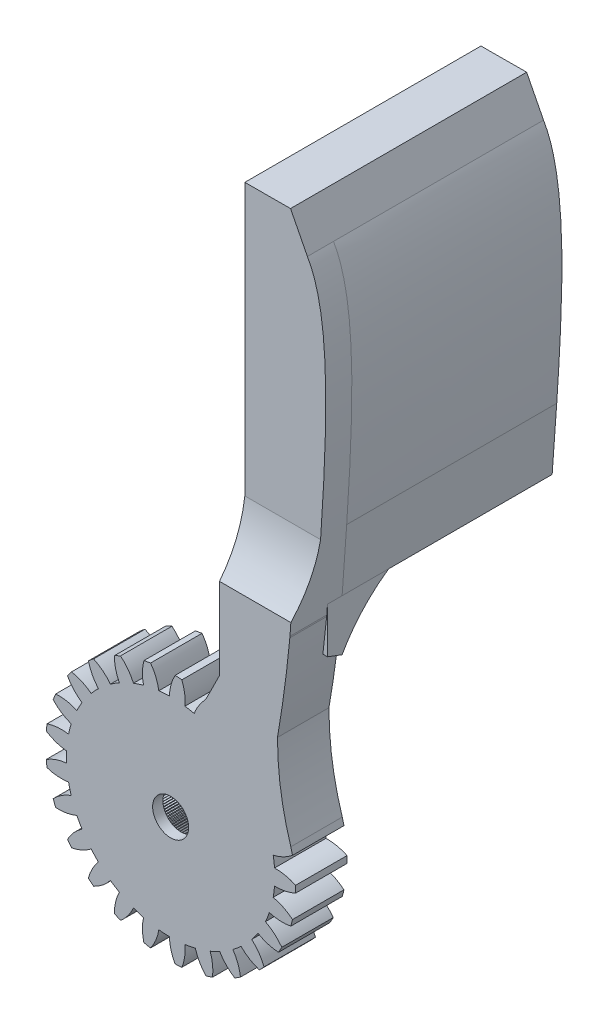
SolidWorks part; units mm, degrees
ref_plane "Front Plane" through (0, 0, 0) normal (0, 0, 1) x (1, 0, 0)
ref_plane "Top Plane" through (0, 0, 0) normal (0, 1, 0) x (1, 0, 0)
ref_plane "Right Plane" through (0, 0, 0) normal (1, 0, 0) x (0, 0, -1)
sketch "Sketch1" plane through (0, 0, 0) normal (0, 0, 1) x (1, 0, 0)
  line L400 (11.1072, 2.7986) -> (11.0109, 2.9361)
  line L401 (11.0109, 2.9361) -> (10.9327, 2.7877)
  line L402 (10.9327, 2.7877) -> (10.828, 2.9188)
  line L403 (10.828, 2.9188) -> (10.7592, 2.7657)
  line L404 (10.7592, 2.7657) -> (10.6465, 2.89)
  line L405 (10.6465, 2.89) -> (10.5874, 2.733)
  line L406 (10.5874, 2.733) -> (10.4672, 2.8499)
  line L407 (10.4672, 2.8499) -> (10.4181, 2.6895)
  line L408 (10.4181, 2.6895) -> (10.2907, 2.7987)
  line L409 (10.2907, 2.7987) -> (10.2518, 2.6355)
  line L410 (10.2518, 2.6355) -> (10.1178, 2.7364)
  line L411 (10.1178, 2.7364) -> (10.0893, 2.5711)
  line L412 (10.0893, 2.5711) -> (9.9492, 2.6635)
  line L413 (9.9492, 2.6635) -> (9.9311, 2.4967)
  line L414 (9.9311, 2.4967) -> (9.7855, 2.58)
  line L415 (9.7855, 2.58) -> (9.7778, 2.4124)
  line L416 (9.7778, 2.4124) -> (9.6273, 2.4865)
  line L417 (9.6273, 2.4865) -> (9.6302, 2.3187)
  line L418 (9.6302, 2.3187) -> (9.4753, 2.3832)
  line L419 (9.4753, 2.3832) -> (9.4888, 2.216)
  line L420 (9.4888, 2.216) -> (9.3301, 2.2706)
  line L421 (9.3301, 2.2706) -> (9.354, 2.1045)
  line L422 (9.354, 2.1045) -> (9.1923, 2.1491)
  line L423 (9.1923, 2.1491) -> (9.2266, 1.9848)
  line L424 (9.2266, 1.9848) -> (9.0624, 2.0191)
  line L425 (9.0624, 2.0191) -> (9.1069, 1.8574)
  line L426 (9.1069, 1.8574) -> (8.9408, 1.8813)
  line L427 (8.9408, 1.8813) -> (8.9955, 1.7227)
  line L428 (8.9955, 1.7227) -> (8.8282, 1.7361)
  line L429 (8.8282, 1.7361) -> (8.8927, 1.5812)
  line L430 (8.8927, 1.5812) -> (8.7249, 1.5841)
  line L431 (8.7249, 1.5841) -> (8.799, 1.4336)
  line L432 (8.799, 1.4336) -> (8.6314, 1.426)
  line L433 (8.6314, 1.426) -> (8.7148, 1.2804)
  line L434 (8.7148, 1.2804) -> (8.548, 1.2623)
  line L435 (8.548, 1.2623) -> (8.6403, 1.1222)
  line L436 (8.6403, 1.1222) -> (8.475, 1.0936)
  line L437 (8.475, 1.0936) -> (8.576, 0.9596)
  line L438 (8.576, 0.9596) -> (8.4128, 0.9207)
  line L439 (8.4128, 0.9207) -> (8.5219, 0.7933)
  line L440 (8.5219, 0.7933) -> (8.3615, 0.7443)
  line L441 (8.3615, 0.7443) -> (8.4785, 0.624)
  line L442 (8.4785, 0.624) -> (8.3214, 0.565)
  line L443 (8.3214, 0.565) -> (8.4457, 0.4522)
  line L444 (8.4457, 0.4522) -> (8.2927, 0.3835)
  line L445 (8.2927, 0.3835) -> (8.4238, 0.2788)
  line L446 (8.4238, 0.2788) -> (8.2754, 0.2005)
  line L447 (8.2754, 0.2005) -> (8.4128, 0.1043)
  line L448 (8.4128, 0.1043) -> (8.2696, 0.0169)
  line L449 (8.2696, 0.0169) -> (8.4128, -0.0706)
  line L450 (8.4128, -0.0706) -> (8.2754, -0.1668)
  line L451 (8.2754, -0.1668) -> (8.4238, -0.245)
  line L452 (8.4238, -0.245) -> (8.2927, -0.3497)
  line L453 (8.2927, -0.3497) -> (8.4457, -0.4185)
  line L454 (8.4457, -0.4185) -> (8.3214, -0.5312)
  line L455 (8.3214, -0.5312) -> (8.4785, -0.5903)
  line L456 (8.4785, -0.5903) -> (8.3615, -0.7105)
  line L457 (8.3615, -0.7105) -> (8.5219, -0.7596)
  line L458 (8.5219, -0.7596) -> (8.4128, -0.887)
  line L459 (8.4128, -0.887) -> (8.576, -0.9259)
  line L460 (8.576, -0.9259) -> (8.475, -1.0599)
  line L461 (8.475, -1.0599) -> (8.6403, -1.0884)
  line L462 (8.6403, -1.0884) -> (8.548, -1.2285)
  line L463 (8.548, -1.2285) -> (8.7148, -1.2466)
  line L464 (8.7148, -1.2466) -> (8.6314, -1.3922)
  line L465 (8.6314, -1.3922) -> (8.799, -1.3999)
  line L466 (8.799, -1.3999) -> (8.7249, -1.5504)
  line L467 (8.7249, -1.5504) -> (8.8927, -1.5475)
  line L468 (8.8927, -1.5475) -> (8.8282, -1.7024)
  line L469 (8.8282, -1.7024) -> (8.9955, -1.6889)
  line L470 (8.9955, -1.6889) -> (8.9408, -1.8476)
  line L471 (8.9408, -1.8476) -> (9.1069, -1.8237)
  line L472 (9.1069, -1.8237) -> (9.0624, -1.9854)
  line L473 (9.0624, -1.9854) -> (9.2266, -1.9511)
  line L474 (9.2266, -1.9511) -> (9.1923, -2.1153)
  line L475 (9.1923, -2.1153) -> (9.354, -2.0708)
  line L476 (9.354, -2.0708) -> (9.3301, -2.2369)
  line L477 (9.3301, -2.2369) -> (9.4888, -2.1822)
  line L478 (9.4888, -2.1822) -> (9.4753, -2.3495)
  line L479 (9.4753, -2.3495) -> (9.6302, -2.285)
  line L480 (9.6302, -2.285) -> (9.6273, -2.4528)
  line L481 (9.6273, -2.4528) -> (9.7778, -2.3787)
  line L482 (9.7778, -2.3787) -> (9.7855, -2.5463)
  line L483 (9.7855, -2.5463) -> (9.9311, -2.4629)
  line L484 (9.9311, -2.4629) -> (9.9492, -2.6297)
  line L485 (9.9492, -2.6297) -> (10.0893, -2.5374)
  line L486 (10.0893, -2.5374) -> (10.1178, -2.7027)
  line L487 (10.1178, -2.7027) -> (10.2518, -2.6017)
  line L488 (10.2518, -2.6017) -> (10.2907, -2.7649)
  line L489 (10.2907, -2.7649) -> (10.4181, -2.6558)
  line L490 (10.4181, -2.6558) -> (10.4672, -2.8162)
  line L491 (10.4672, -2.8162) -> (10.5874, -2.6992)
  line L492 (10.5874, -2.6992) -> (10.6465, -2.8563)
  line L493 (10.6465, -2.8563) -> (10.7592, -2.732)
  line L494 (10.7592, -2.732) -> (10.828, -2.885)
  line L495 (10.828, -2.885) -> (10.9327, -2.7539)
  line L496 (10.9327, -2.7539) -> (11.0109, -2.9023)
  line L497 (11.0109, -2.9023) -> (11.1072, -2.7649)
  line L498 (11.1072, -2.7649) -> (11.1946, -2.9081)
  line L499 (11.1946, -2.9081) -> (11.282, -2.7649)
  line L500 (11.282, -2.7649) -> (11.3782, -2.9023)
  line L501 (11.3782, -2.9023) -> (11.4565, -2.7539)
  line L502 (11.4565, -2.7539) -> (11.5612, -2.885)
  line L503 (11.5612, -2.885) -> (11.6299, -2.732)
  line L504 (11.6299, -2.732) -> (11.7427, -2.8563)
  line L505 (11.7427, -2.8563) -> (11.8017, -2.6992)
  line L506 (11.8017, -2.6992) -> (11.922, -2.8162)
  line L507 (11.922, -2.8162) -> (11.971, -2.6558)
  line L508 (11.971, -2.6558) -> (12.0984, -2.7649)
  line L509 (12.0984, -2.7649) -> (12.1373, -2.6017)
  line L510 (12.1373, -2.6017) -> (12.2713, -2.7027)
  line L511 (12.2713, -2.7027) -> (12.2999, -2.5374)
  line L512 (12.2999, -2.5374) -> (12.44, -2.6297)
  line L513 (12.44, -2.6297) -> (12.4581, -2.4629)
  line L514 (12.4581, -2.4629) -> (12.6037, -2.5463)
  line L515 (12.6037, -2.5463) -> (12.6113, -2.3787)
  line L516 (12.6113, -2.3787) -> (12.7618, -2.4528)
  line L517 (12.7618, -2.4528) -> (12.7589, -2.285)
  line L518 (12.7589, -2.285) -> (12.9138, -2.3495)
  line L519 (12.9138, -2.3495) -> (12.9004, -2.1822)
  line L520 (12.9004, -2.1822) -> (13.059, -2.2369)
  line L521 (13.059, -2.2369) -> (13.0351, -2.0708)
  line L522 (13.0351, -2.0708) -> (13.1968, -2.1153)
  line L523 (13.1968, -2.1153) -> (13.1625, -1.9511)
  line L524 (13.1625, -1.9511) -> (13.3268, -1.9854)
  line L525 (13.3268, -1.9854) -> (13.2822, -1.8237)
  line L526 (13.2822, -1.8237) -> (13.4483, -1.8476)
  line L527 (13.4483, -1.8476) -> (13.3937, -1.6889)
  line L528 (13.3937, -1.6889) -> (13.5609, -1.7024)
  line L529 (13.5609, -1.7024) -> (13.4965, -1.5475)
  line L530 (13.4965, -1.5475) -> (13.6642, -1.5504)
  line L531 (13.6642, -1.5504) -> (13.5901, -1.3999)
  line L532 (13.5901, -1.3999) -> (13.7577, -1.3922)
  line L533 (13.7577, -1.3922) -> (13.6744, -1.2466)
  line L534 (13.6744, -1.2466) -> (13.8412, -1.2285)
  line L535 (13.8412, -1.2285) -> (13.7488, -1.0884)
  line L536 (13.7488, -1.0884) -> (13.9141, -1.0599)
  line L537 (13.9141, -1.0599) -> (13.8132, -0.9259)
  line L538 (13.8132, -0.9259) -> (13.9764, -0.887)
  line L539 (13.9764, -0.887) -> (13.8672, -0.7596)
  line L540 (13.8672, -0.7596) -> (14.0276, -0.7105)
  line L541 (14.0276, -0.7105) -> (13.9107, -0.5903)
  line L542 (13.9107, -0.5903) -> (14.0677, -0.5312)
  line L543 (14.0677, -0.5312) -> (13.9434, -0.4185)
  line L544 (13.9434, -0.4185) -> (14.0965, -0.3497)
  line L545 (14.0965, -0.3497) -> (13.9654, -0.245)
  line L546 (13.9654, -0.245) -> (14.1138, -0.1668)
  line L547 (14.1138, -0.1668) -> (13.9763, -0.0706)
  line L548 (13.9763, -0.0706) -> (14.1195, 0.0169)
  line L549 (14.1195, 0.0169) -> (13.9763, 0.1043)
  line L550 (13.9763, 0.1043) -> (14.1138, 0.2005)
  line L551 (14.1138, 0.2005) -> (13.9654, 0.2788)
  line L552 (13.9654, 0.2788) -> (14.0965, 0.3835)
  line L553 (14.0965, 0.3835) -> (13.9434, 0.4522)
  line L554 (13.9434, 0.4522) -> (14.0677, 0.565)
  line L555 (14.0677, 0.565) -> (13.9107, 0.624)
  line L556 (13.9107, 0.624) -> (14.0276, 0.7443)
  line L557 (14.0276, 0.7443) -> (13.8672, 0.7933)
  line L558 (13.8672, 0.7933) -> (13.9764, 0.9207)
  line L559 (13.9764, 0.9207) -> (13.8132, 0.9596)
  line L560 (13.8132, 0.9596) -> (13.9141, 1.0936)
  line L561 (13.9141, 1.0936) -> (13.7488, 1.1222)
  line L562 (13.7488, 1.1222) -> (13.8412, 1.2623)
  line L563 (13.8412, 1.2623) -> (13.6744, 1.2804)
  line L564 (13.6744, 1.2804) -> (13.7577, 1.426)
  line L565 (13.7577, 1.426) -> (13.5901, 1.4336)
  line L566 (13.5901, 1.4336) -> (13.6642, 1.5841)
  line L567 (13.6642, 1.5841) -> (13.4965, 1.5812)
  line L568 (13.4965, 1.5812) -> (13.5609, 1.7361)
  line L569 (13.5609, 1.7361) -> (13.3937, 1.7227)
  line L570 (13.3937, 1.7227) -> (13.4483, 1.8813)
  line L571 (13.4483, 1.8813) -> (13.2822, 1.8574)
  line L572 (13.2822, 1.8574) -> (13.3268, 2.0191)
  line L573 (13.3268, 2.0191) -> (13.1625, 1.9848)
  line L574 (13.1625, 1.9848) -> (13.1968, 2.1491)
  line L575 (13.1968, 2.1491) -> (13.0351, 2.1045)
  line L576 (13.0351, 2.1045) -> (13.059, 2.2706)
  line L577 (13.059, 2.2706) -> (12.9004, 2.216)
  line L578 (12.9004, 2.216) -> (12.9138, 2.3832)
  line L579 (12.9138, 2.3832) -> (12.7589, 2.3187)
  line L580 (12.7589, 2.3187) -> (12.7618, 2.4865)
  line L581 (12.7618, 2.4865) -> (12.6113, 2.4124)
  line L582 (12.6113, 2.4124) -> (12.6037, 2.58)
  line L583 (12.6037, 2.58) -> (12.4581, 2.4967)
  line L584 (12.4581, 2.4967) -> (12.44, 2.6635)
  line L585 (12.44, 2.6635) -> (12.2999, 2.5711)
  line L586 (12.2999, 2.5711) -> (12.2713, 2.7364)
  line L587 (12.2713, 2.7364) -> (12.1373, 2.6355)
  line L588 (12.1373, 2.6355) -> (12.0984, 2.7987)
  line L589 (12.0984, 2.7987) -> (11.971, 2.6895)
  line L590 (11.971, 2.6895) -> (11.922, 2.8499)
  line L591 (11.922, 2.8499) -> (11.8017, 2.733)
  line L592 (11.8017, 2.733) -> (11.7427, 2.89)
  line L593 (11.7427, 2.89) -> (11.6299, 2.7657)
  line L594 (11.6299, 2.7657) -> (11.5612, 2.9188)
  line L595 (11.5612, 2.9188) -> (11.4565, 2.7877)
  line L596 (11.4565, 2.7877) -> (11.3782, 2.9361)
  line L597 (11.3782, 2.9361) -> (11.282, 2.7986)
  line L598 (11.282, 2.7986) -> (11.1946, 2.9418)
  line L599 (11.1946, 2.9418) -> (11.1072, 2.7986)
  circle A1 centre (11.1946, 0) radius 1.8
  arc A202 (10.0473, 10.0588) -> (9.2444, 11.9925) centre (5.6039, 9.3473) ccw
  arc A203 (9.2444, 11.9925) -> (8.5931, 11.8682) centre (11.1946, 0) ccw
  arc A204 (8.5931, 11.8682) -> (8.5584, 9.7748) centre (12.9517, 10.749) ccw
  arc A205 (8.5584, 9.7748) -> (7.5818, 9.4575) centre (11.1946, 0) ccw
  arc A206 (7.5818, 9.4575) -> (6.3233, 11.1307) centre (3.455, 7.6633) ccw
  arc A207 (6.3233, 11.1307) -> (5.7233, 10.8484) centre (11.1946, 0) ccw
  arc A208 (5.7233, 10.8484) -> (6.2103, 8.8121) centre (10.2233, 10.8483) ccw
  arc A209 (6.2103, 8.8121) -> (5.3434, 8.2619) centre (11.1946, 0) ccw
  arc A210 (5.3434, 8.2619) -> (3.7082, 9.5696) centre (1.7923, 5.4978) ccw
  arc A211 (3.7082, 9.5696) -> (3.1973, 9.1469) centre (11.1946, 0) ccw
  arc A212 (3.1973, 9.1469) -> (4.1754, 7.2957) centre (7.556, 10.2659) ccw
  arc A213 (4.1754, 7.2957) -> (3.4725, 6.5472) centre (11.1946, 0) ccw
  arc A214 (3.4725, 6.5472) -> (1.5636, 7.4072) centre (0.7205, 2.9868) ccw
  arc A215 (1.5636, 7.4072) -> (1.1738, 6.8707) centre (11.1946, 0) ccw
  arc A216 (1.1738, 6.8707) -> (2.5816, 5.3209) centre (5.1172, 9.0385) ccw
  arc A217 (2.5816, 5.3209) -> (2.0869, 4.4211) centre (11.1946, 0) ccw
  arc A218 (2.0869, 4.4211) -> (0.024, 4.7793) centre (0.3067, 0.2882) ccw
  arc A219 (0.024, 4.7793) -> (-0.2201, 4.1628) centre (11.1946, 0) ccw
  arc A220 (-0.2201, 4.1628) -> (1.5289, 3.0118) centre (3.0604, 7.2432) ccw
  arc A221 (1.5289, 3.0118) -> (1.2736, 2.0172) centre (11.1946, 0) ccw
  arc A222 (1.2736, 2.0172) -> (-0.8136, 1.8512) centre (0.5771, -2.4286) ccw
  arc A223 (-0.8136, 1.8512) -> (-0.8967, 1.1933) centre (11.1946, 0) ccw
  arc A224 (-0.8967, 1.1933) -> (1.0836, 0.5134) centre (1.5146, 4.9927) ccw
  arc A225 (1.0836, 0.5134) -> (1.0836, -0.5134) centre (11.1946, 0) ccw
  arc A226 (1.0836, -0.5134) -> (-0.8967, -1.1933) centre (1.5146, -4.9927) ccw
  arc A227 (-0.8967, -1.1933) -> (-0.8136, -1.8512) centre (11.1946, 0) ccw
  arc A228 (-0.8136, -1.8512) -> (1.2736, -2.0172) centre (0.5771, 2.4286) ccw
  arc A229 (1.2736, -2.0172) -> (1.5289, -3.0118) centre (11.1946, 0) ccw
  arc A230 (1.5289, -3.0118) -> (-0.2201, -4.1628) centre (3.0604, -7.2432) ccw
  arc A231 (-0.2201, -4.1628) -> (0.024, -4.7793) centre (11.1946, 0) ccw
  arc A232 (0.024, -4.7793) -> (2.0869, -4.4211) centre (0.3067, -0.2882) ccw
  arc A233 (2.0869, -4.4211) -> (2.5816, -5.3209) centre (11.1946, 0) ccw
  arc A234 (2.5816, -5.3209) -> (1.1738, -6.8707) centre (5.1172, -9.0385) ccw
  arc A235 (1.1738, -6.8707) -> (1.5636, -7.4072) centre (11.1946, 0) ccw
  arc A236 (1.5636, -7.4072) -> (3.4725, -6.5472) centre (0.7205, -2.9868) ccw
  arc A237 (3.4725, -6.5472) -> (4.1754, -7.2957) centre (11.1946, 0) ccw
  arc A238 (4.1754, -7.2957) -> (3.1973, -9.1469) centre (7.556, -10.2659) ccw
  arc A239 (3.1973, -9.1469) -> (3.7082, -9.5696) centre (11.1946, 0) ccw
  arc A240 (3.7082, -9.5696) -> (5.3434, -8.2619) centre (1.7923, -5.4978) ccw
  arc A241 (5.3434, -8.2619) -> (6.2103, -8.8121) centre (11.1946, 0) ccw
  arc A242 (6.2103, -8.8121) -> (5.7233, -10.8484) centre (10.2233, -10.8483) ccw
  arc A243 (5.7233, -10.8484) -> (6.3233, -11.1307) centre (11.1946, 0) ccw
  arc A244 (6.3233, -11.1307) -> (7.5818, -9.4575) centre (3.455, -7.6633) ccw
  arc A245 (7.5818, -9.4575) -> (8.5584, -9.7748) centre (11.1946, 0) ccw
  arc A246 (8.5584, -9.7748) -> (8.5931, -11.8682) centre (12.9517, -10.749) ccw
  arc A247 (8.5931, -11.8682) -> (9.2444, -11.9925) centre (11.1946, 0) ccw
  arc A248 (9.2444, -11.9925) -> (10.0473, -10.0588) centre (5.6039, -9.3473) ccw
  arc A249 (10.0473, -10.0588) -> (11.0721, -10.1233) centre (11.1946, 0) ccw
  arc A250 (11.0721, -10.1233) -> (11.6263, -12.1423) centre (15.5696, -9.9743) ccw
  arc A251 (11.6263, -12.1423) -> (12.2881, -12.1007) centre (11.1946, 0) ccw
  arc A252 (12.2881, -12.1007) -> (12.5849, -10.0281) centre (8.1041, -10.444) ccw
  arc A253 (12.5849, -10.0281) -> (13.5935, -9.8357) centre (11.1946, 0) ccw
  arc A254 (13.5935, -9.8357) -> (14.6324, -11.6535) centre (17.9127, -8.5729) ccw
  arc A255 (14.6324, -11.6535) -> (15.263, -11.4486) centre (11.1946, 0) ccw
  arc A256 (15.263, -11.4486) -> (15.0351, -9.3673) centre (10.7985, -10.8845) ccw
  arc A257 (15.0351, -9.3673) -> (15.9642, -8.9301) centre (11.1946, 0) ccw
  arc A258 (15.9642, -8.9301) -> (17.4225, -10.4324) centre (19.8336, -6.6329) ccw
  arc A259 (17.4225, -10.4324) -> (17.9824, -10.0771) centre (11.1946, 0) ccw
  arc A260 (17.9824, -10.0771) -> (17.244, -8.1179) centre (13.5178, -10.641) ccw
  arc A261 (17.244, -8.1179) -> (18.0351, -7.4634) centre (11.1946, 0) ccw
  arc A262 (18.0351, -7.4634) -> (19.8213, -8.5558) centre (21.2117, -4.276) ccw
  arc A263 (19.8213, -8.5558) -> (20.2752, -8.0725) centre (11.1946, 0) ccw
  arc A264 (20.2752, -8.0725) -> (19.0727, -6.3584) centre (16.0912, -9.7289) ccw
  arc A265 (19.0727, -6.3584) -> (19.6763, -5.5277) centre (11.1946, 0) ccw
  arc A266 (19.6763, -5.5277) -> (21.678, -6.1417) centre (21.9604, -1.6505) ccw
  arc A267 (21.678, -6.1417) -> (21.9975, -5.5606) centre (11.1946, 0) ccw
  arc A268 (21.9975, -5.5606) -> (20.4065, -4.1994) centre (18.3568, -8.2055) ccw
  arc A269 (20.4065, -4.1994) -> (20.7845, -3.2447) centre (11.1946, 0) ccw
  arc A270 (20.7845, -3.2447) -> (22.876, -3.3416) centre (22.0327, 1.0787) ccw
  arc A271 (22.876, -3.3416) -> (23.0409, -2.6993) centre (11.1946, 0) ccw
  arc A272 (23.0409, -2.6993) -> (21.1615, -1.7766) centre (20.1724, -6.1666) ccw
  arc A273 (21.1615, -1.7766) -> (21.2902, -0.7579) centre (11.1946, 0) ccw
  arc A274 (21.2902, -0.7579) -> (23.34, -0.3315) centre (21.4239, 3.7401) ccw
  arc A275 (23.34, -0.3315) -> (23.34, 0.3315) centre (11.1946, 0) ccw
  arc A276 (23.34, 0.3315) -> (21.2902, 0.7579) centre (21.4239, -3.7401) ccw
  arc A277 (21.2902, 0.7579) -> (21.1615, 1.7766) centre (11.1946, 0) ccw
  arc A278 (21.1615, 1.7766) -> (23.0409, 2.6993) centre (20.1724, 6.1666) ccw
  arc A279 (23.0409, 2.6993) -> (22.876, 3.3416) centre (11.1946, 0) ccw
  arc A280 (22.876, 3.3416) -> (20.7845, 3.2447) centre (22.0327, -1.0787) ccw
  arc A281 (20.7845, 3.2447) -> (20.4065, 4.1994) centre (11.1946, 0) ccw
  arc A282 (20.4065, 4.1994) -> (21.9975, 5.5606) centre (18.3568, 8.2055) ccw
  arc A283 (21.9975, 5.5606) -> (21.678, 6.1417) centre (11.1946, 0) ccw
  arc A284 (21.678, 6.1417) -> (19.6763, 5.5277) centre (21.9604, 1.6505) ccw
  arc A285 (19.6763, 5.5277) -> (19.0727, 6.3584) centre (11.1946, 0) ccw
  arc A286 (19.0727, 6.3584) -> (20.2752, 8.0725) centre (16.0912, 9.7289) ccw
  arc A287 (20.2752, 8.0725) -> (19.8213, 8.5558) centre (11.1946, 0) ccw
  arc A288 (19.8213, 8.5558) -> (18.0351, 7.4634) centre (21.2117, 4.276) ccw
  arc A289 (18.0351, 7.4634) -> (17.244, 8.1179) centre (11.1946, 0) ccw
  arc A290 (17.244, 8.1179) -> (17.9824, 10.0771) centre (13.5178, 10.641) ccw
  arc A291 (17.9824, 10.0771) -> (17.4225, 10.4324) centre (11.1946, 0) ccw
  arc A292 (17.4225, 10.4324) -> (15.9642, 8.9301) centre (19.8336, 6.6329) ccw
  arc A293 (15.9642, 8.9301) -> (15.0351, 9.3673) centre (11.1946, 0) ccw
  arc A294 (15.0351, 9.3673) -> (15.263, 11.4486) centre (10.7985, 10.8845) ccw
  arc A295 (15.263, 11.4486) -> (14.6324, 11.6535) centre (11.1946, 0) ccw
  arc A296 (14.6324, 11.6535) -> (13.5935, 9.8357) centre (17.9127, 8.5729) ccw
  arc A297 (13.5935, 9.8357) -> (12.5849, 10.0281) centre (11.1946, 0) ccw
  arc A298 (12.5849, 10.0281) -> (12.2881, 12.1007) centre (8.1041, 10.444) ccw
  arc A299 (12.2881, 12.1007) -> (11.6263, 12.1423) centre (11.1946, 0) ccw
  arc A300 (11.6263, 12.1423) -> (11.0721, 10.1233) centre (15.5696, 9.9743) ccw
  arc A301 (11.0721, 10.1233) -> (10.0473, 10.0588) centre (11.1946, 0) ccw
extrude "Boss-Extrude1" add sketch "Sketch1" against normal blind 3.5 and the other way blind 1.5 contours A300 A301 A202 A203 A204 A205 A206 A207 A208 A209 A210 A211 A212 A213 A214 A215 A216 A217 A218 A219 A220 A221 A222 A223 A224 A225 A226 A227 A228 A229 A230 A231 A232 A233 A234 A235 A236 A237 A238 A239 A240 A241 A242 A243 A244 A245 A246 A247 A248 A249 A250
sketch "Sketch2" plane through (0, 0, 1.5) normal (0, 0, 1) x (1, 0, 0)
  circle A0 centre (11.1946, 0) radius 4.0084
  circle A1 centre (11.1946, 0) radius 1.75
  point P4 (0, 0)
  point P5 (11.1946, 0)
  dimension "D1" = 3.5
extrude "Boss-Extrude2" add sketch "Sketch2" against normal blind 1
sketch "Sketch3" plane through (0, 0, 1.5) normal (0, 0, 1) x (1, 0, 0)
  line L1 (15.9423, 22.4702) -> (15.9423, 14.2911)
  line L2 (15.9423, 22.4702) -> (15.9423, 11.8958) construction
  line L3 (22.0239, 51.3696) -> (20.3829, 54.5854)
  line L4 (20.3829, 54.5854) -> (15.9423, 54.57)
  line L5 (15.9423, 54.57) -> (15.9423, 22.4869)
  line L6 (22.0239, 51.3696) -> (20.3829, 54.5854)
  line L7 (20.3829, 54.5854) -> (15.9423, 54.57)
  line L8 (15.9423, 54.57) -> (15.9423, 22.4702)
  arc A1 (22.7797, 20.8786) -> (22.7928, 21.0188) centre (-93.0857, 31.7468) ccw
  arc A2 (22.7797, 20.8786) -> (22.7928, 21.0188) centre (-93.0857, 31.7468) ccw
  parabola Q1 (15.9423, 22.4869) -> (22.7797, 20.8786) focus (19.545, 22.4006) apex (19.058, 20.291)
  parabola Q3 (21.5807, 11.8958) -> (22.7797, 20.8786) focus (-35.1591, 21.052) apex (21.3357, 10.5344)
  spline S0 degree 2 poles (21.5807, 11.8958) (21.5698, 7.5097) (22.876, 3.3416) knots 0 0 0 1 1 1
  spline S1 degree 3 poles (532.1862, 881.5493) (-497.081, -1087.2666) (534.895, 1124.9549) (-463.0428, -823.1001) knots -2.370021 -2.370021 -2.370021 -2.370021 2.826333 2.826333 2.826333 2.826333 only from (22.7928, 21.0188) to (22.0239, 51.3696)
  spline S2 degree 3 poles (22.7928, 21.0188) (23.7105, 33.7464) (24.8314, 46.6712) (22.0239, 51.3696) knots 0.222416 0.222416 0.222416 0.222416 0.743755 0.743755 0.743755 0.743755
  spline S3 degree 1 poles (15.9423, 14.2911) (14.6324, 11.6535) knots 0 0 1 1
  spline S4 degree 3 poles (14.6324, 11.6535) (9.7915, 6.5032) (18.1537, -1.0996) (22.876, 3.3416) knots 0 0 0 0 1 1 1 1
  dimension "D1" = 0
extrude "Boss-Extrude3" add sketch "Sketch3" against normal up to surface (5 mm away) up to face at (11.1946, 0.0169, -3.5)
sketch "Sketch4" plane through (0, 0, -3.5) normal (0, 0, -1) x (-1, 0, 0)
  line L0 (-22.8613, 21.9652) -> (-15.9423, 21.9652) construction
  line L1 (-15.9423, 21.9652) -> (-15.9423, 28.1734) construction
  line L2 (-15.9423, 28.1734) -> (-15.9423, 54.57) construction
  line L3 (-15.9423, 54.57) -> (-20.3829, 54.5854) construction
  line L4 (-20.3829, 54.5854) -> (-22.0239, 51.3696) construction
  line L5 (-22.8613, 21.9652) -> (-15.9423, 21.9652)
  line L6 (-15.9423, 21.9652) -> (-15.9423, 28.1734)
  line L7 (-15.9423, 28.1734) -> (-15.9423, 54.57)
  line L8 (-15.9423, 54.57) -> (-20.3829, 54.5854)
  line L9 (-20.3829, 54.5854) -> (-22.0239, 51.3696)
  circle A4 centre (-19.8677, 42.255) radius 1.7 construction
  circle A5 centre (-19.4255, 30.0015) radius 1.7 construction
  circle A6 centre (-19.8677, 42.255) radius 1.7
  circle A7 centre (-19.4255, 30.0015) radius 1.7
  spline S0 degree 3 poles (924.0731, -1732.4632) (-999.8701, 2089.3078) (961.3262, -2043.337) (-991.3678, 1770.7659) knots -2.49157 -2.49157 -2.49157 -2.49157 3.951559 3.951559 3.951559 3.951559 only from (-23.3052, 28.1734) to (-22.8613, 21.9652) construction
  spline S1 degree 3 poles (915.2571, -1714.9526) (-994.701, 2078.3139) (960.0354, -2041.078) (-993.9172, 1775.7456) knots -2.481698 -2.481698 -2.481698 -2.481698 3.954361 3.954361 3.954361 3.954361 only from (-22.0239, 51.3696) to (-23.3052, 28.1734) construction
  spline S2 degree 3 poles (-23.3052, 28.1734) (-23.1666, 26.1289) (-23.0126, 24.0472) (-22.8613, 21.9652) knots 0.645586 0.645586 0.645586 0.645586 0.730836 0.730836 0.730836 0.730836
  spline S3 degree 3 poles (-22.0239, 51.3696) (-24.3027, 47.5559) (-23.9933, 38.3222) (-23.3052, 28.1734) knots 0.222416 0.222416 0.222416 0.222416 0.645586 0.645586 0.645586 0.645586
extrude "Boss-Extrude4" add sketch "Sketch4" along normal blind 20.4145
sketch "Sketch5" plane through (0, 0, 0) normal (1, 0, 0) x (0, 0, -1)
  line L1 (47.8233, 28.1734) -> (47.8233, 51.3696)
  line L2 (0.9637, 28.1734) -> (0.9637, 51.3696)
  line L4 (24.3935, 21.9652) -> (24.3935, 31.9862) construction
  line L5 (0.9637, 51.3696) -> (0.9637, 55.6372)
  line L6 (0.9637, 55.6372) -> (-3.2678, 55.1385)
  line L7 (-3.2678, 55.1385) -> (-5.311, 33.3947)
  line L8 (-5.311, 33.3947) -> (-1.7043, 21.9652)
  parabola Q1 (47.8233, 28.1734) -> (50.4914, 21.9652) focus (54.098, 26.7593) apex (49.0224, 24.181)
  parabola Q2 (0.9637, 28.1734) -> (-1.7043, 21.9652) focus (-5.311, 26.7593) apex (-0.2353, 24.181)
extrude "Cut-Extrude1" cut sketch "Sketch5" along normal blind 38.6833 contours Q2 L2 L5 L6 L7 L8
sketch "Sketch6" plane through (15.9423, 0, 0) normal (-1, 0, 0) x (0, 0, 1)
  line L0 (-23.9145, 21.9652) -> (-3.5, 21.9652) construction
  line L1 (-3.5, 20.8786) -> (-3.5, 11.8958) construction
  line L2 (-8.0171, 21.9652) -> (-2.0768, 23.3081)
  line L3 (-2.0768, 23.3081) -> (-2.0768, 17.5356)
  line L4 (-2.0768, 17.5356) -> (-3.5, 16.9986)
  spline S0 degree 2 poles (-8.0171, 21.9652) (-5.1996, 20.0051) (-3.5, 16.9986) knots 0 0 0 1 1 1
extrude "Boss-Extrude6" add sketch "Sketch6" against normal up to vertex
sketch "Sketch7" plane through (0, 0, 1.5) normal (0, 0, 1) x (1, 0, 0)
  line L0 (10.5589, -10.104) -> (10.3356, -13.5375) construction
  arc A0 (10.0473, -10.0588) -> (11.0721, -10.1233) centre (11.1946, 0) ccw construction
